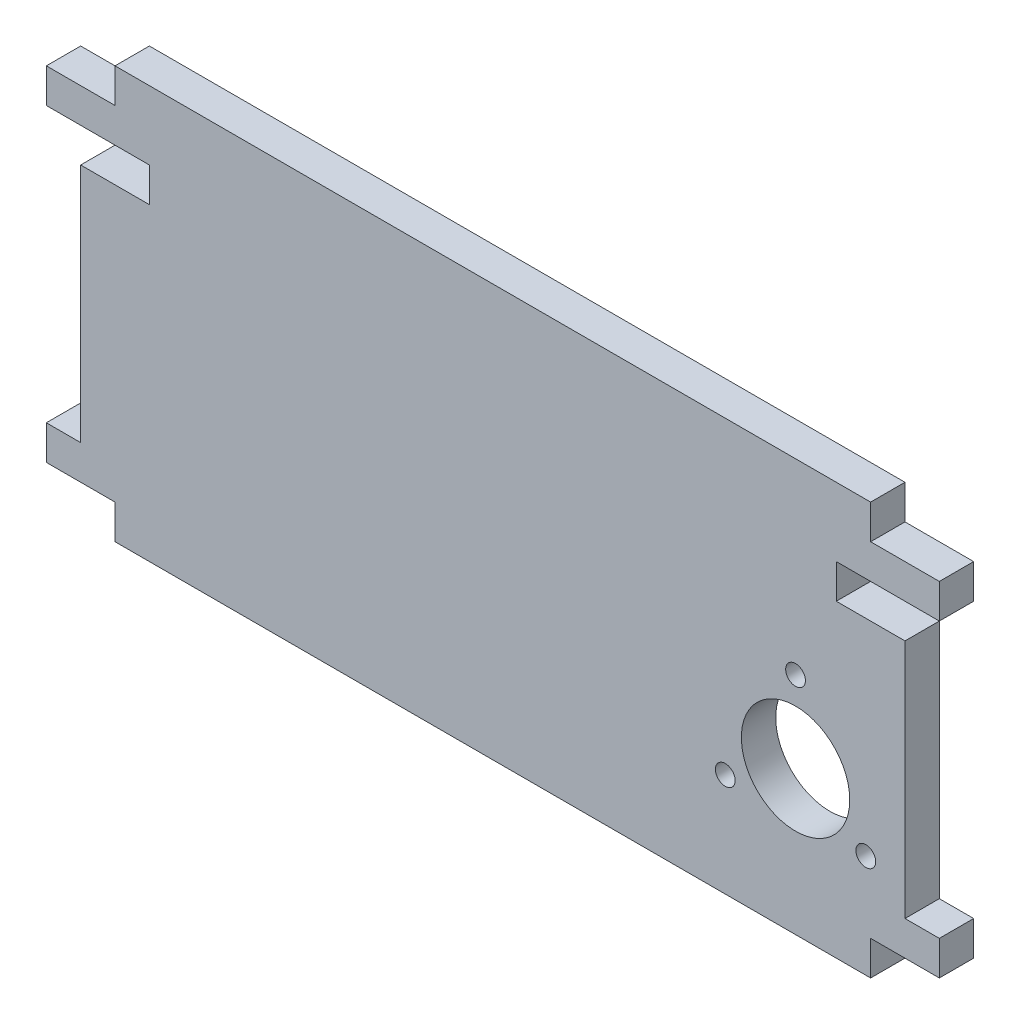
SolidWorks part; units mm, degrees
ref_plane "Front Plane" through (0, 0, 0) normal (0, 0, 1) x (1, 0, 0)
ref_plane "Top Plane" through (0, 0, 0) normal (0, 1, 0) x (1, 0, 0)
ref_plane "Right Plane" through (0, 0, 0) normal (1, 0, 0) x (0, 0, -1)
sketch "Sketch1" plane through (0, 0, 0) normal (0, 0, 1) x (1, 0, 0)
  line L0 (-95.25, -3.175) -> (44.45, -3.175)
  line L1 (44.45, -3.175) -> (44.45, 3.175)
  line L2 (44.45, 3.175) -> (57.15, 3.175)
  line L3 (57.15, 3.175) -> (57.15, 9.525)
  line L4 (57.15, 9.525) -> (50.8, 9.525)
  line L5 (50.8, 9.525) -> (50.8, 60.325)
  line L6 (50.8, 60.325) -> (57.15, 60.325)
  line L7 (57.15, 60.325) -> (57.15, 66.675)
  line L8 (57.15, 66.675) -> (44.45, 66.675)
  line L9 (44.45, 66.675) -> (44.45, 73.025)
  line L10 (44.45, 73.025) -> (-95.25, 73.025)
  line L11 (-95.25, 73.025) -> (-95.25, 66.675)
  line L12 (-95.25, 66.675) -> (-107.95, 66.675)
  line L13 (-107.95, 66.675) -> (-107.95, 60.325)
  line L14 (-107.95, 60.325) -> (-101.6, 60.325)
  line L15 (-101.6, 60.325) -> (-101.6, 9.525)
  line L16 (-101.6, 9.525) -> (-107.95, 9.525)
  line L17 (-107.95, 9.525) -> (-107.95, 3.175)
  line L18 (-107.95, 3.175) -> (-95.25, 3.175)
  line L19 (-95.25, 3.175) -> (-95.25, -3.175)
  dimension "D1" = 6.35
extrude "Boss-Extrude1" add sketch "Sketch1" along normal up to surface (6.35 mm away)
sketch "Sketch2" plane through (0, 0, 6.35) normal (0, 0, 1) x (1, 0, 0)
  line L4 (57.15, 60.325) -> (38.1, 60.325)
  line L5 (38.1, 60.325) -> (38.1, 53.975)
  line L6 (38.1, 53.975) -> (57.15, 53.975)
  line L7 (57.15, 53.975) -> (57.15, 60.325)
  line L8 (57.15, 60.325) -> (38.1, 60.325)
  line L9 (38.1, 60.325) -> (38.1, 53.975)
  line L10 (38.1, 53.975) -> (57.15, 53.975)
  line L11 (57.15, 53.975) -> (57.15, 60.325)
  line L12 (-88.9, 60.325) -> (-107.95, 60.325)
  line L13 (-107.95, 60.325) -> (-107.95, 53.975)
  line L14 (-107.95, 53.975) -> (-88.9, 53.975)
  line L15 (-88.9, 53.975) -> (-88.9, 60.325)
  line L16 (-88.9, 60.325) -> (-107.95, 60.325)
  line L17 (-107.95, 60.325) -> (-107.95, 53.975)
  line L18 (-107.95, 53.975) -> (-88.9, 53.975)
  line L19 (-88.9, 53.975) -> (-88.9, 60.325)
  circle A0 centre (30.5689, 38.4061) radius 1.8288 construction
  circle A1 centre (30.5689, 23.4061) radius 10.0203
  circle A2 centre (30.5689, 23.4061) radius 10.0203
  circle A3 centre (17.5785, 15.9061) radius 1.8288 construction
  circle A4 centre (43.5593, 15.9061) radius 1.8288 construction
  circle A5 centre (30.5689, 38.4061) radius 1.8288
  circle A6 centre (17.5785, 15.9061) radius 1.8288
  circle A7 centre (43.5593, 15.9061) radius 1.8288
  dimension "D1" = 0
  dimension "D2" = 0
  dimension "D3" = 0
extrude "Cut-Extrude1" cut sketch "Sketch2" against normal through all
